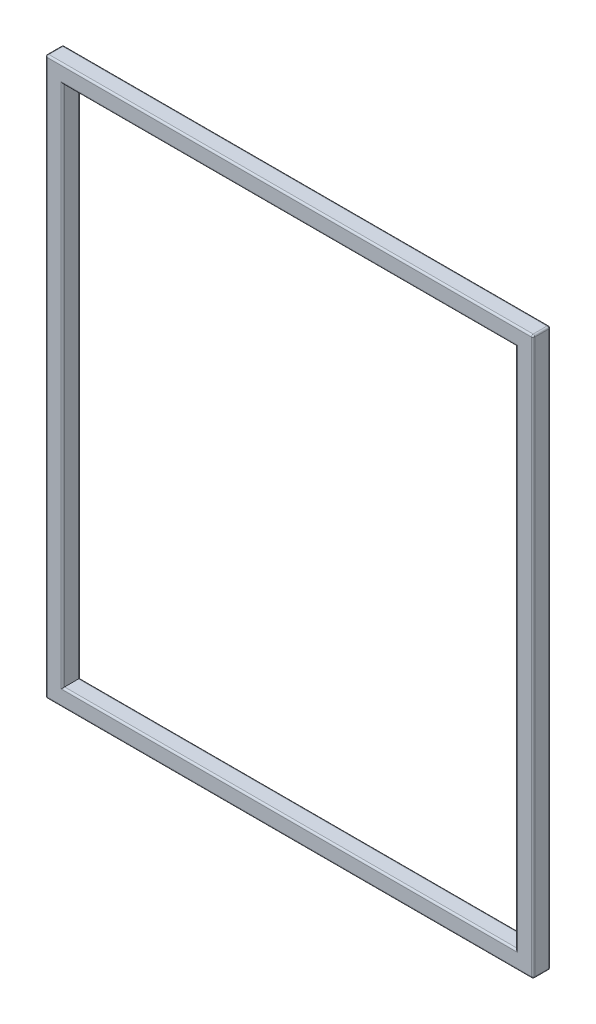
SolidWorks part; units mm, degrees
material "6061 Alloy"
ref_plane "Front" through (0, 0, 0) normal (0, 0, 1) x (1, 0, 0)
ref_plane "Top" through (0, 0, 0) normal (0, 1, 0) x (1, 0, 0)
ref_plane "Right" through (0, 0, 0) normal (1, 0, 0) x (0, 0, -1)
sketch "Sketch1" plane through (0, 0, 0) normal (0, 0, 1) x (1, 0, 0)
  line L1 (0, 0) -> (-711.2, 0)
  line L2 (0, 0) -> (0, 812.8)
  line L3 (0, 812.8) -> (-711.2, 812.8)
  line L4 (-711.2, 0) -> (-711.2, 812.8)
  line L5 (-25.4, 25.4) -> (-685.8, 25.4)
  line L6 (-25.4, 25.4) -> (-25.4, 787.4)
  line L7 (-25.4, 787.4) -> (-685.8, 787.4)
  line L8 (-685.8, 25.4) -> (-685.8, 787.4)
  dimension "D1" = 711.2
  dimension "D2" = 812.8
  dimension "D3" = 25.4
  dimension "D4" = 25.4
  dimension "D5" = 25.4
  dimension "D6" = 25.4
extrude "Boss-Extrude1" add sketch "Sketch1" along normal blind 25.4
fillet "Fillet1" radius 2.54 20 edges at (-25.4, 406.4, 0) (-355.6, 787.4, 0) (-685.8, 406.4, 0) (-355.6, 25.4, 0) (-25.4, 406.4, 25.4) (-355.6, 787.4, 25.4) (-685.8, 406.4, 25.4) (-355.6, 25.4, 25.4) (0, 406.4, 0) (-355.6, 812.8, 0) (-711.2, 406.4, 0) (-355.6, 0, 0) (0, 406.4, 25.4) (-355.6, 812.8, 25.4) (-711.2, 406.4, 25.4) (-355.6, 0, 25.4) (0, 0, 12.7) (-711.2, 0, 12.7) (-711.2, 812.8, 12.7) (0, 812.8, 12.7)
